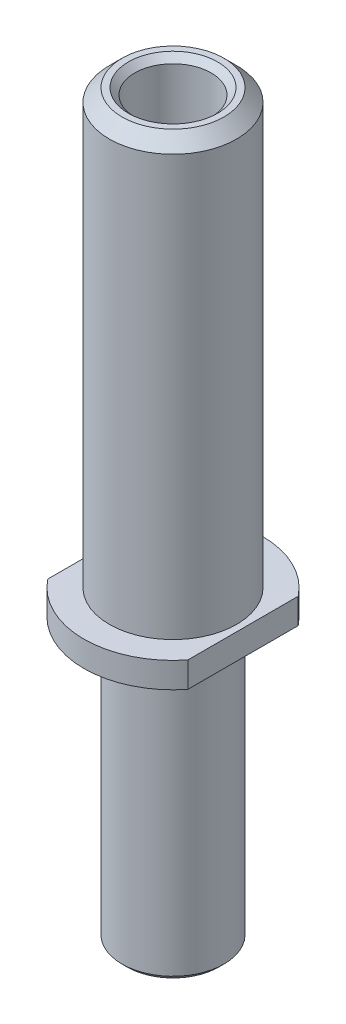
SolidWorks part; units mm, degrees
material "Chrome Stainless Steel"
ref_plane "Front Plane" through (0, 0, 0) normal (0, 0, 1) x (1, 0, 0)
ref_plane "Top Plane" through (0, 0, 0) normal (0, 1, 0) x (1, 0, 0)
ref_plane "Right Plane" through (0, 0, 0) normal (1, 0, 0) x (0, 0, -1)
sketch "Sketch1" plane through (0, 0, 0) normal (1, 0, 0) x (0, 0, -1)
  line L0 (0, 29) -> (0, 0) construction
  line L1 (-1.5, 0.2) -> (-1.5, 28.75)
  line L2 (-1.5, 29) -> (0, 29) construction
  line L3 (-1.5, 0) -> (0, 0) construction
  line L4 (-1.75, 29) -> (-2, 29)
  line L5 (-2.5, 28.5) -> (-2.5, 12)
  line L6 (-1.7, 0) -> (-1.8, 0)
  line L7 (-2, 0.2) -> (-2, 11)
  line L8 (-2, 11) -> (-3.5, 11)
  line L9 (-3.5, 11) -> (-3.5, 12)
  line L10 (-3.5, 12) -> (-2.5, 12)
  line L11 (-1.5, 28.75) -> (-1.75, 29)
  line L12 (-2, 29) -> (-2.5, 28.5)
  line L13 (-1.7, 0) -> (-1.5, 0.2)
  line L14 (-1.8, 0) -> (-2, 0.2)
  point P6 (-2.5, 29)
  point P8 (-2, 0)
  dimension "D1" = 29
  dimension "D2" = 1.5
  dimension "D3" = 2.5
  dimension "D4" = 2
  dimension "D5" = 1
  dimension "D6" = 3.5
  dimension "D11" = 11
revolve "Revolve1" add sketch "Sketch1" angle 360 about L0
sketch "Sketch2" plane through (0, 0, 0) normal (0, 1, 0) x (1, 0, 0)
  line L0 (-2.75, 2.1651) -> (-2.75, -2.1651)
  line L1 (2.75, 2.1651) -> (2.75, -2.1651)
  circle A0 centre (0, 0) radius 3.5 construction
  arc A1 (-2.75, 2.1651) -> (-2.75, -2.1651) centre (0, 0) ccw
  arc A2 (2.75, -2.1651) -> (2.75, 2.1651) centre (0, 0) ccw
  dimension "D1" = 2.75
  dimension "D2" = 2.75
extrude "Cut-Extrude1" cut sketch "Sketch2" along normal up to next
